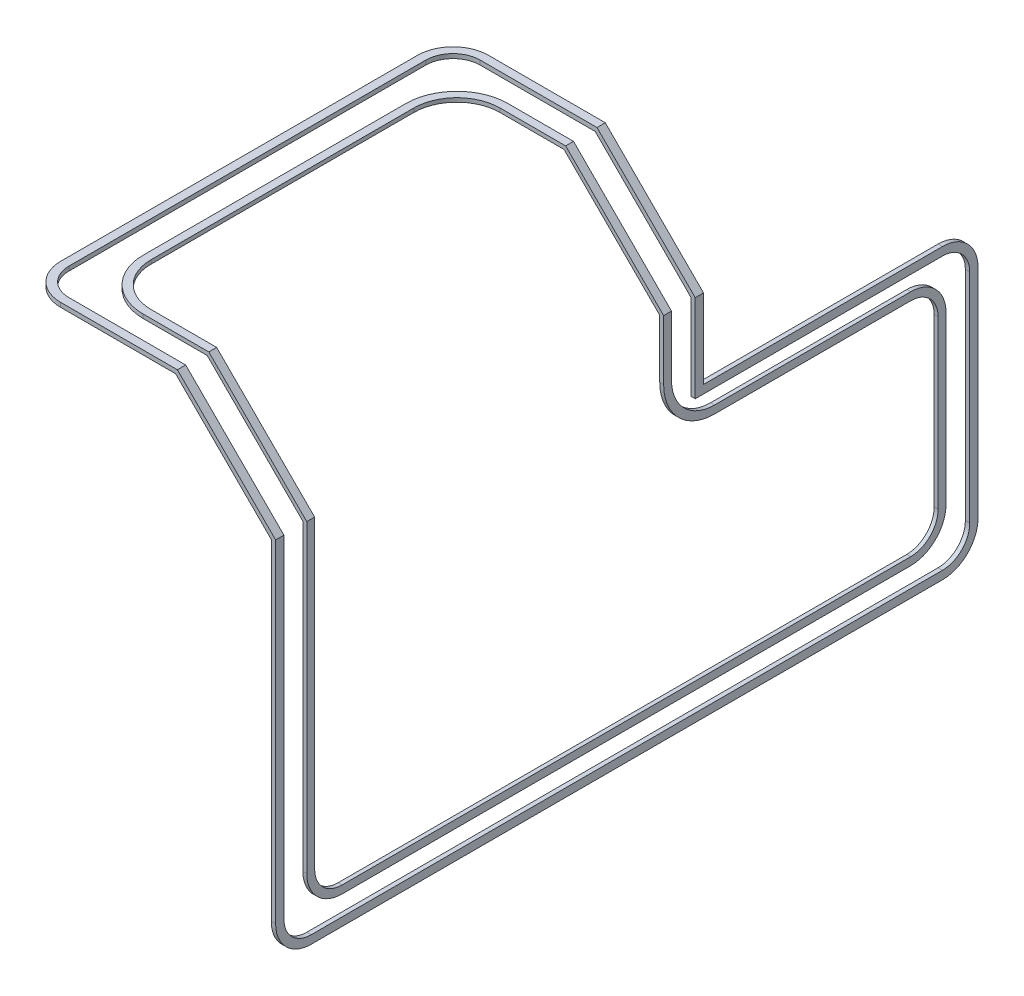
SolidWorks part; units mm, degrees
material "ASTM A36 Steel"
ref_plane "Front Plane" through (0, 0, 0) normal (0, 0, 1) x (1, 0, 0)
ref_plane "Top Plane" through (0, 0, 0) normal (0, 1, 0) x (1, 0, 0)
ref_plane "Right Plane" through (0, 0, 0) normal (1, 0, 0) x (0, 0, -1)
ref_plane "Plane1" through (141.986, 0, 0) normal (1, 0, 0) x (0, 0, -1)
ref_plane "Plane2" through (0, 141.986, 0) normal (0, 1, 0) x (-1, 0, 0)
sketch "Sketch1" plane through (141.986, 0, 0) normal (1, 0, 0) x (0, 0, -1)
  line L0 (11.1252, 64.516) -> (11.1252, -203.2)
  line L1 (36.5252, -228.6) -> (547.6748, -228.6)
  line L2 (573.0748, -203.2) -> (573.0748, -26.9875)
  line L3 (547.6748, -1.5875) -> (350.8502, -1.5875)
  line L4 (350.8502, -1.5875) -> (350.8502, 64.516)
  line L5 (36.5252, 64.516) -> (36.5252, -180.975)
  line L6 (61.9252, -206.375) -> (522.2748, -206.375)
  line L7 (547.6748, -180.975) -> (547.6748, -46.0375)
  line L8 (522.2748, -20.6375) -> (363.5502, -20.6375)
  line L9 (325.4502, 64.516) -> (325.4502, 17.4625)
  arc A1 (573.0748, -26.9875) -> (547.6748, -1.5875) centre (547.6748, -26.9875) ccw
  arc A2 (547.6748, -228.6) -> (573.0748, -203.2) centre (547.6748, -203.2) ccw
  arc A3 (11.1252, -203.2) -> (36.5252, -228.6) centre (36.5252, -203.2) ccw
  arc A5 (36.5252, -180.975) -> (61.9252, -206.375) centre (61.9252, -180.975) ccw
  arc A8 (522.2748, -206.375) -> (547.6748, -180.975) centre (522.2748, -180.975) ccw
  arc A11 (547.6748, -46.0375) -> (522.2748, -20.6375) centre (522.2748, -46.0375) ccw
  arc A13 (363.5502, -20.6375) -> (325.4502, 17.4625) centre (363.5502, 17.4625) cw
  dimension "D1" = 25.4
  dimension "D8" = 25.4
  dimension "D20" = 38.1
  dimension "D2" = 11.1252
  dimension "D3" = 228.6
  dimension "D4" = 1.5875
  dimension "D5" = 561.9496
  dimension "D6" = 339.725
  dimension "D7" = 64.516
  dimension "D11" = 22.225
  dimension "D12" = 25.4
  dimension "D17" = 19.05
  dimension "D18" = 25.4
  dimension "D19" = 25.4
sketch "Sketch3" plane through (0, 141.986, 0) normal (0, 1, 0) x (-1, 0, 0)
  line L0 (-64.516, -11.1252) -> (28.575, -11.1252)
  line L1 (53.975, -36.5252) -> (53.975, -325.4502)
  line L2 (28.575, -350.8502) -> (-64.516, -350.8502)
  line L3 (-64.516, -36.5252) -> (-12.7, -36.5252)
  line L4 (25.4, -74.6252) -> (25.4, -287.3502)
  line L5 (-12.7, -325.4502) -> (-64.516, -325.4502)
  arc A0 (53.975, -325.4502) -> (28.575, -350.8502) centre (28.575, -325.4502) cw
  arc A1 (28.575, -11.1252) -> (53.975, -36.5252) centre (28.575, -36.5252) cw
  arc A2 (-12.7, -36.5252) -> (25.4, -74.6252) centre (-12.7, -74.6252) cw
  arc A3 (25.4, -287.3502) -> (-12.7, -325.4502) centre (-12.7, -287.3502) cw
  dimension "D1" = 25.4
  dimension "D4" = 38.1
  dimension "D2" = 64.516
  dimension "D3" = 53.975
  dimension "D7" = 28.575
sketch3d "3DSketch1"
  line L0 (141.986, 64.516, -11.1252) -> (141.986, -203.2, -11.1252) construction
  line L1 (141.986, -228.6, -36.5252) -> (141.986, -228.6, -547.6748) construction
  line L2 (141.986, -203.2, -573.0748) -> (141.986, -26.9875, -573.0748) construction
  line L3 (141.986, -1.5875, -547.6748) -> (141.986, -1.5875, -350.8502) construction
  line L4 (141.986, -1.5875, -350.8502) -> (141.986, 64.516, -350.8502) construction
  line L5 (141.986, 64.516, -11.1252) -> (141.986, -203.2, -11.1252)
  line L6 (141.986, -228.6, -36.5252) -> (141.986, -228.6, -547.6748)
  line L7 (141.986, -203.2, -573.0748) -> (141.986, -26.9875, -573.0748)
  line L8 (141.986, -1.5875, -547.6748) -> (141.986, -1.5875, -350.8502)
  line L9 (141.986, -1.5875, -350.8502) -> (141.986, 64.516, -350.8502)
  line L10 (-28.575, 141.986, -350.8502) -> (64.516, 141.986, -350.8502) construction
  line L11 (-53.975, 141.986, -36.5252) -> (-53.975, 141.986, -325.4502) construction
  line L12 (64.516, 141.986, -11.1252) -> (-28.575, 141.986, -11.1252) construction
  line L13 (-28.575, 141.986, -350.8502) -> (64.516, 141.986, -350.8502)
  line L14 (-53.975, 141.986, -36.5252) -> (-53.975, 141.986, -325.4502)
  line L15 (64.516, 141.986, -11.1252) -> (-28.575, 141.986, -11.1252)
  line L16 (64.516, 141.986, -11.1252) -> (141.986, 64.516, -11.1252)
  line L17 (64.516, 141.986, -350.8502) -> (141.986, 64.516, -350.8502)
  arc A0 (141.986, -203.2, -11.1252) -> (141.986, -228.6, -36.5252) centre (141.986, -203.2, -36.5252) ccw construction
  arc A1 (141.986, -228.6, -547.6748) -> (141.986, -203.2, -573.0748) centre (141.986, -203.2, -547.6748) ccw construction
  arc A2 (141.986, -26.9875, -573.0748) -> (141.986, -1.5875, -547.6748) centre (141.986, -26.9875, -547.6748) ccw construction
  arc A4 (141.986, -203.2, -11.1252) -> (141.986, -228.6, -36.5252) centre (141.986, -203.2, -36.5252) ccw
  arc A5 (141.986, -228.6, -547.6748) -> (141.986, -203.2, -573.0748) centre (141.986, -203.2, -547.6748) ccw
  arc A6 (141.986, -26.9875, -573.0748) -> (141.986, -1.5875, -547.6748) centre (141.986, -26.9875, -547.6748) ccw
  arc A8 (-53.975, 141.986, -325.4502) -> (-28.575, 141.986, -350.8502) centre (-28.575, 141.986, -325.4502) ccw construction
  arc A9 (-28.575, 141.986, -11.1252) -> (-53.975, 141.986, -36.5252) centre (-28.575, 141.986, -36.5252) ccw construction
  arc A10 (-53.975, 141.986, -325.4502) -> (-28.575, 141.986, -350.8502) centre (-28.575, 141.986, -325.4502) ccw
  arc A11 (-28.575, 141.986, -11.1252) -> (-53.975, 141.986, -36.5252) centre (-28.575, 141.986, -36.5252) ccw
  point P5 (167.386, -203.2, -36.5252)
  point P9 (167.386, -203.2, -547.6748)
  point P13 (167.386, -26.9875, -547.6748)
  point P15 (167.386, -203.2, -36.5252)
  point P19 (167.386, -203.2, -547.6748)
  point P20 (167.386, -26.9875, -547.6748)
  point P27 (-28.575, 116.586, -325.4502)
  point P31 (-28.575, 116.586, -36.5252)
  point P32 (-28.575, 116.586, -325.4502)
  point P33 (-28.575, 116.586, -36.5252)
  point P34 (141.986, 0, -11.1252)
sketch "Sketch4" plane through (0, 0, 0) normal (0, 1, 0) x (0, 0, -1)
  line L1 (7.7724, -145.5166) -> (14.478, -145.5166)
  line L2 (7.7724, -145.5166) -> (7.7724, -141.986)
  line L3 (7.7724, -141.986) -> (14.478, -141.986)
  line L4 (14.478, -145.5166) -> (14.478, -141.986)
  dimension "D1" = 6.7056
  dimension "D2" = 3.5306
sweep "Sweep1" add profiles "Sketch4" path "3DSketch1"
sketch3d "3DSketch2"
  line L0 (141.986, -20.6375, -522.2748) -> (141.986, -20.6375, -363.5502) construction
  line L1 (141.986, 64.516, -36.5252) -> (141.986, -180.975, -36.5252) construction
  line L2 (141.986, -206.375, -61.9252) -> (141.986, -206.375, -522.2748) construction
  line L3 (141.986, -180.975, -547.6748) -> (141.986, -46.0375, -547.6748) construction
  line L4 (-25.4, 141.986, -74.6252) -> (-25.4, 141.986, -287.3502) construction
  line L5 (141.986, 64.516, -325.4502) -> (141.986, 17.4625, -325.4502) construction
  line L6 (141.986, 64.516, -36.5252) -> (141.986, -180.975, -36.5252)
  line L7 (141.986, -206.375, -61.9252) -> (141.986, -206.375, -522.2748)
  line L8 (141.986, -180.975, -547.6748) -> (141.986, -46.0375, -547.6748)
  line L9 (141.986, -20.6375, -522.2748) -> (141.986, -20.6375, -363.5502)
  line L10 (141.986, 64.516, -325.4502) -> (141.986, 17.4625, -325.4502)
  line L11 (64.516, 141.986, -36.5252) -> (12.7, 141.986, -36.5252) construction
  line L13 (12.7, 141.986, -325.4502) -> (64.516, 141.986, -325.4502) construction
  line L14 (64.516, 141.986, -36.5252) -> (12.7, 141.986, -36.5252)
  line L16 (12.7, 141.986, -325.4502) -> (64.516, 141.986, -325.4502)
  line L17 (64.516, 141.986, -36.5252) -> (141.986, 64.516, -36.5252)
  line L18 (64.516, 141.986, -325.4502) -> (141.986, 64.516, -325.4502)
  line L19 (-25.4, 141.986, -74.6252) -> (-25.4, 141.986, -287.3502)
  arc A1 (141.986, -180.975, -36.5252) -> (141.986, -206.375, -61.9252) centre (141.986, -180.975, -61.9252) ccw construction
  arc A4 (141.986, -206.375, -522.2748) -> (141.986, -180.975, -547.6748) centre (141.986, -180.975, -522.2748) ccw construction
  arc A7 (141.986, -46.0375, -547.6748) -> (141.986, -20.6375, -522.2748) centre (141.986, -46.0375, -522.2748) ccw construction
  arc A10 (141.986, -180.975, -36.5252) -> (141.986, -206.375, -61.9252) centre (141.986, -180.975, -61.9252) ccw
  arc A13 (141.986, -206.375, -522.2748) -> (141.986, -180.975, -547.6748) centre (141.986, -180.975, -522.2748) ccw
  arc A16 (141.986, -46.0375, -547.6748) -> (141.986, -20.6375, -522.2748) centre (141.986, -46.0375, -522.2748) ccw
  arc A18 (12.7, 141.986, -36.5252) -> (-25.4, 141.986, -74.6252) centre (12.7, 141.986, -74.6252) ccw construction
  arc A19 (-25.4, 141.986, -287.3502) -> (12.7, 141.986, -325.4502) centre (12.7, 141.986, -287.3502) ccw construction
  arc A20 (12.7, 141.986, -36.5252) -> (-25.4, 141.986, -74.6252) centre (12.7, 141.986, -74.6252) ccw
  arc A21 (-25.4, 141.986, -287.3502) -> (12.7, 141.986, -325.4502) centre (12.7, 141.986, -287.3502) ccw
  arc A22 (141.986, -20.6375, -363.5502) -> (141.986, 17.4625, -325.4502) centre (141.986, 17.4625, -363.5502) ccw construction
  arc A23 (141.986, -20.6375, -363.5502) -> (141.986, 17.4625, -325.4502) centre (141.986, 17.4625, -363.5502) ccw
  point P8 (167.386, -180.975, -61.9252)
  point P18 (167.386, -180.975, -522.2748)
  point P28 (167.386, -46.0375, -522.2748)
  point P34 (167.386, -180.975, -61.9252)
  point P37 (167.386, -180.975, -522.2748)
  point P40 (167.386, -46.0375, -522.2748)
  point P47 (12.7, 103.886, -74.6252)
  point P49 (12.7, 103.886, -74.6252)
  point P51 (12.7, 103.886, -287.3502)
  point P53 (12.7, 103.886, -287.3502)
  point P54 (141.986, 0, -36.5252)
  point P57 (103.886, 17.4625, -363.5502)
  point P58 (103.886, 17.4625, -363.5502)
sketch "Sketch5" plane through (0, 0, 0) normal (0, 1, 0) x (1, 0, 0)
  line L1 (141.986, 33.3502) -> (145.161, 33.3502)
  line L2 (141.986, 33.3502) -> (141.986, 39.7002)
  line L3 (141.986, 39.7002) -> (145.161, 39.7002)
  line L4 (145.161, 33.3502) -> (145.161, 39.7002)
  dimension "D1" = 6.35
  dimension "D2" = 3.175
sweep "Sweep2" add profiles "Sketch5" path "3DSketch2"
